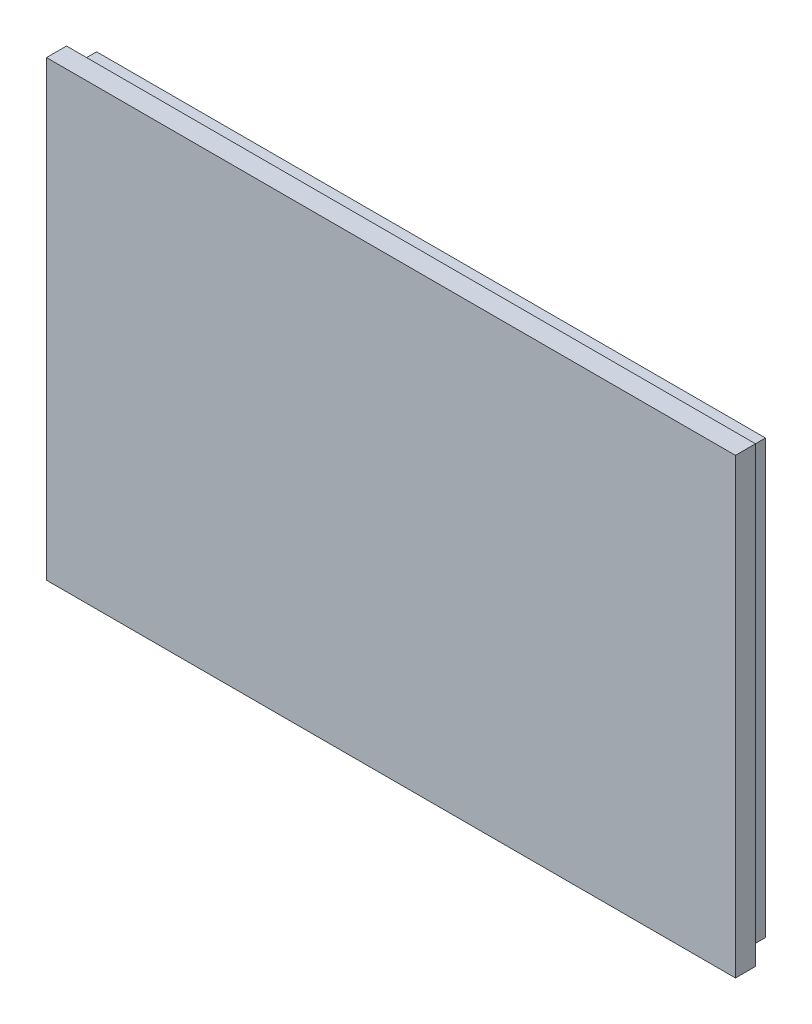
SolidWorks part; units mm, degrees
ref_plane "Front Plane" through (0, 0, 0) normal (0, 0, 1) x (1, 0, 0)
ref_plane "Top Plane" through (0, 0, 0) normal (0, 1, 0) x (1, 0, 0)
ref_plane "Right Plane" through (0, 0, 0) normal (1, 0, 0) x (0, 0, -1)
sketch "Sketch1" plane through (0, 0, 0) normal (0, 0, 1) x (1, 0, 0)
  line L1 (-17.2, -11.3) -> (17.2, -11.3)
  line L2 (-17.2, -11.3) -> (-17.2, 11.3)
  line L3 (-17.2, 11.3) -> (17.2, 11.3)
  line L4 (17.2, -11.3) -> (17.2, 11.3)
  line L5 (-17.2, -11.3) -> (17.2, 11.3) construction
  line L6 (-17.2, 11.3) -> (17.2, -11.3) construction
  point P0 (0, 0)
  dimension "D1" = 34.4
  dimension "D2" = 22.6
extrude "Boss-Extrude1" add sketch "Sketch1" along normal blind 1
sketch "Sketch2" plane through (0, 0, 0) normal (0, 0, -1) x (-1, 0, 0)
  line L1 (-16.7, -10.8) -> (16.7, -10.8)
  line L2 (-16.7, -10.8) -> (-16.7, 10.8)
  line L3 (-16.7, 10.8) -> (16.7, 10.8)
  line L4 (16.7, -10.8) -> (16.7, 10.8)
  line L5 (-16.7, -10.8) -> (16.7, 10.8) construction
  line L6 (-16.7, 10.8) -> (16.7, -10.8) construction
  point P0 (0, 0)
  dimension "D1" = 33.4
  dimension "D2" = 21.6
extrude "Boss-Extrude2" add sketch "Sketch2" along normal blind 1
